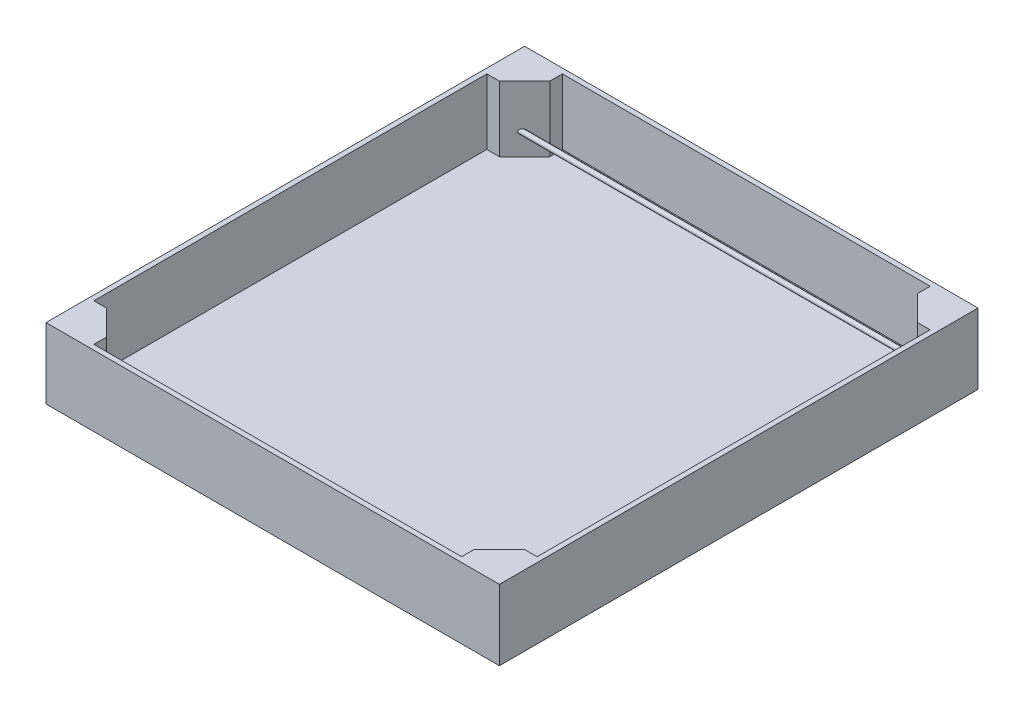
SolidWorks part; units mm, degrees
ref_plane "Front Plane" through (0, 0, 0) normal (0, 0, 1) x (1, 0, 0)
ref_plane "Top Plane" through (0, 0, 0) normal (0, 1, 0) x (1, 0, 0)
ref_plane "Right Plane" through (0, 0, 0) normal (1, 0, 0) x (0, 0, -1)
sketch "Sketch3" plane through (0, 0, 0) normal (0, 1, 0) x (1, 0, 0)
  line L1 (0, 0) -> (457.2, 0)
  line L2 (0, 0) -> (0, 482.6)
  line L3 (0, 482.6) -> (457.2, 482.6)
  line L4 (457.2, 0) -> (457.2, 482.6)
  dimension "D1" = 482.6
  dimension "D2" = 457.2
extrude "Boss-Extrude2" add sketch "Sketch3" along normal blind 5.08 contours L2 L1 L4 L3
sketch "Sketch4" plane through (0, 5.08, 0) normal (0, 1, 0) x (1, 0, 0)
  line L1 (0, 0) -> (457.2, 0)
  line L2 (0, 0) -> (0, 482.6)
  line L3 (0, 482.6) -> (457.2, 482.6)
  line L4 (457.2, 0) -> (457.2, 482.6)
  line L5 (5.08, 5.08) -> (452.12, 5.08)
  line L6 (5.08, 5.08) -> (5.08, 477.52)
  line L7 (5.08, 477.52) -> (452.12, 477.52)
  line L8 (452.12, 5.08) -> (452.12, 477.52)
  point P10 (0, 0)
  dimension "D1" = 472.44
  dimension "D2" = 447.04
  dimension "D3" = 5.08
  dimension "D4" = 5.08
extrude "Boss-Extrude3" add sketch "Sketch4" along normal blind 66.04
sketch "Sketch5" plane through (0, 5.08, 0) normal (0, 1, 0) x (1, 0, 0)
  line L0 (5.08, 5.08) -> (43.2082, 5.08)
  line L1 (5.08, 5.08) -> (452.12, 5.08) construction
  line L2 (43.2082, 5.08) -> (43.2082, 17.78)
  line L3 (43.2082, 17.78) -> (17.78, 43.18)
  line L4 (17.78, 43.18) -> (5.08, 43.18)
  line L5 (5.08, 43.18) -> (5.08, 5.08)
  line L6 (5.08, 477.52) -> (5.08, 5.08) construction
  point P7 (5.08, 43.4243)
  point P9 (17.3496, 43.5495)
  point P10 (5.08, 5.8419)
  dimension "D1" = 38.1
  dimension "D2" = 12.7
  dimension "D3" = 12.7
  dimension "D4" = 35.941
extrude "Boss-Extrude4" add sketch "Sketch5" along normal blind 66.04
sketch "Sketch6" plane through (0, 5.08, 0) normal (0, 1, 0) x (1, 0, 0)
  line L0 (452.12, 5.08) -> (414.02, 5.08)
  line L1 (43.2082, 5.08) -> (452.12, 5.08) construction
  line L2 (414.02, 5.08) -> (414.02, 17.78)
  line L3 (414.02, 17.78) -> (439.42, 43.1118)
  line L4 (439.42, 43.1118) -> (452.12, 43.1118)
  line L5 (452.12, 43.1118) -> (452.12, 5.08)
  line L6 (452.12, 5.08) -> (452.12, 477.52) construction
  point P6 (452.12, 46.1859)
  point P11 (441.7331, 43.1118)
  dimension "D1" = 12.7
  dimension "D2" = 38.0318
  dimension "D3" = 38.1
  dimension "D4" = 35.8728
extrude "Boss-Extrude5" add sketch "Sketch6" along normal blind 66.04
sketch "Sketch7" plane through (0, 5.08, 0) normal (0, 1, 0) x (1, 0, 0)
  line L0 (452.12, 477.52) -> (452.12, 439.42)
  line L1 (452.12, 43.1118) -> (452.12, 477.52) construction
  line L2 (452.12, 439.42) -> (439.42, 439.42)
  line L3 (452.12, 477.52) -> (414.0888, 477.52)
  line L4 (452.12, 477.52) -> (5.08, 477.52) construction
  line L5 (414.0888, 477.52) -> (414.0888, 464.82)
  line L6 (414.0888, 464.82) -> (439.42, 439.42)
  point P10 (195.9625, 524.7402)
  dimension "D1" = 12.7
  dimension "D2" = 12.7
  dimension "D4" = 38.1
  dimension "D5" = 38.0312
extrude "Boss-Extrude6" add sketch "Sketch7" along normal blind 66.04 contours L6 L2 L0 L3 L5
sketch "Sketch8" plane through (0, 5.08, 0) normal (0, 1, 0) x (1, 0, 0)
  line L0 (5.08, 477.52) -> (5.08, 439.42)
  line L1 (5.08, 477.52) -> (5.08, 43.18) construction
  line L2 (5.08, 439.42) -> (17.78, 439.42)
  line L3 (5.08, 477.52) -> (43.18, 477.52)
  line L4 (414.0888, 477.52) -> (5.08, 477.52) construction
  line L5 (43.18, 477.52) -> (43.18, 464.82)
  line L6 (43.18, 464.82) -> (17.78, 439.42)
  dimension "D1" = 12.7
  dimension "D2" = 12.7
  dimension "D3" = 38.1
  dimension "D4" = 38.1
extrude "Boss-Extrude7" add sketch "Sketch8" along normal blind 66.04
sketch "Sketch13" plane through (5.08, 0, 0) normal (1, 0, 0) x (0, 0, -1)
  circle A0 centre (33.5107, 26.9472) radius 2.5
  circle A1 centre (451.0213, 26.9472) radius 2.5
  point P4 (51.141, 36.1768)
  point P5 (39.2425, 36.1768)
  point P6 (32.1542, 36.5151)
  point P7 (30.8254, 26.9472)
  point P8 (448.336, 26.9472)
extrude "Boss-Extrude11" add sketch "Sketch13" along normal blind 447.04
